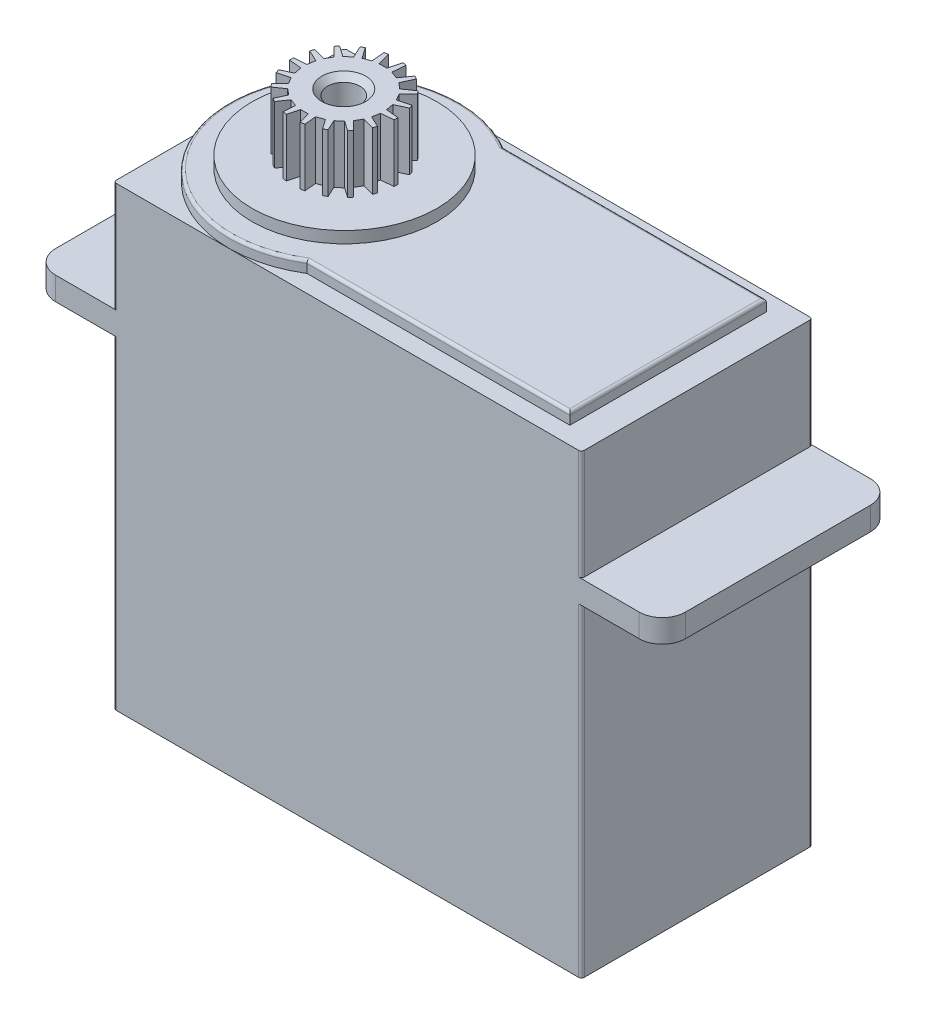
SolidWorks part; units mm, degrees
ref_plane "Plan de face" through (0, 0, 0) normal (0, 0, 1) x (1, 0, 0)
ref_plane "Plan de dessus" through (0, 0, 0) normal (0, 1, 0) x (1, 0, 0)
ref_plane "Plan de droite" through (0, 0, 0) normal (1, 0, 0) x (0, 0, -1)
sketch "Esquisse1" plane through (0, 0, 0) normal (0, 0, 1) x (1, 0, 0)
  line L1 (-20.25, -19.75) -> (20.25, -19.75)
  line L2 (-20.25, -19.75) -> (-20.25, 19.75)
  line L3 (-20.25, 19.75) -> (20.25, 19.75)
  line L4 (20.25, -19.75) -> (20.25, 19.75)
  line L5 (-20.25, -19.75) -> (20.25, 19.75) construction
  line L6 (-20.25, 19.75) -> (20.25, -19.75) construction
  point P0 (0, 0)
  dimension "D1" = 40.5
  dimension "D2" = 39.5
extrude "Boss.-Extru.1" add sketch "Esquisse1" along normal blind 20
sketch "Esquisse2" plane through (-20.25, 0, 0) normal (-1, 0, 0) x (0, 0, 1)
  line L0 (0, 8.25) -> (20, 8.25)
  line L1 (0, 19.75) -> (0, -19.75) construction
  line L2 (20, 19.75) -> (20, -19.75) construction
  line L3 (20, -19.75) -> (0, -19.75) construction
  line L4 (0, 10.25) -> (20, 10.25)
  line L5 (0, 8.25) -> (0, 10.25)
  line L6 (20, 8.25) -> (20, 10.25)
  dimension "D1" = 28
  dimension "D2" = 2
extrude "Boss.-Extru.2" add sketch "Esquisse2" along normal blind 7
sketch "Esquisse3" plane through (20.25, 0, 0) normal (1, 0, 0) x (0, 0, -1)
  line L1 (-20, -19.75) -> (0, -19.75) construction
  line L7 (-20, 8.25) -> (0, 8.25)
  line L8 (-20, -19.75) -> (-20, 19.75) construction
  line L9 (0, -19.75) -> (0, 19.75) construction
  line L10 (0, 8.25) -> (0, 10.25)
  line L11 (0, 10.25) -> (-20, 10.25)
  line L12 (-20, 10.25) -> (-20, 8.25)
  dimension "D1" = 28
  dimension "D2" = 2
extrude "Boss.-Extru.3" add sketch "Esquisse3" along normal blind 7
fillet "Congé1" radius 2 4 edges at (27.25, 9.25, 0) (27.25, 9.25, 20) (-27.25, 9.25, 0) (-27.25, 9.25, 20)
sketch "Esquisse4" plane through (0, 19.75, 0) normal (0, 1, 0) x (1, 0, 0)
  line L0 (-20.25, -10) -> (20.25, -10) construction
  line L1 (-20.25, -20) -> (-20.25, 0) construction
  line L2 (20.25, 0) -> (20.25, -20) construction
  line L3 (17.75, -1.5) -> (17.75, -18.5)
  line L4 (20.25, 0) -> (-20.25, 0) construction
  line L5 (20.25, -20) -> (-20.25, -20) construction
  line L6 (17.75, -1.5) -> (-5.0016, -1.5)
  line L7 (17.75, -18.5) -> (-5.0016, -18.5)
  arc A0 (-5.0016, -1.5) -> (-5.0016, -18.5) centre (-10.25, -10) ccw
  dimension "D1" = 10
  dimension "D2" = 1.5
  dimension "D3" = 1.5
  dimension "D4" = 2.5
extrude "Boss.-Extru.4" add sketch "Esquisse4" along normal blind 1
sketch "Esquisse6" plane through (0, 20.75, 0) normal (0, 1, 0) x (1, 0, 0)
  circle A0 centre (-10.25, -10) radius 8
extrude "Boss.-Extru.5" add sketch "Esquisse6" along normal blind 1
sketch "Esquisse7" plane through (0, 21.75, 0) normal (0, 1, 0) x (1, 0, 0)
  circle A0 centre (-10.25, -10) radius 4.5
extrude "Boss.-Extru.6" add sketch "Esquisse7" along normal blind 5
sketch "Esquisse8" plane through (0, 26.75, 0) normal (0, 1, 0) x (1, 0, 0)
  line L0 (-10.6064, -6.6566) -> (-10.9035, -5.5477)
  line L3 (-10.6064, -6.6566) -> (-9.9401, -6.6566)
  line L7 (-9.9401, -6.6566) -> (-9.6413, -5.5414)
  circle A1 centre (-10.25, -10) radius 4.5
  arc A2 (-9.6413, -5.5414) -> (-10.9035, -5.5477) centre (-10.25, -10) ccw
  point P0 (-10.25, -5.5)
  dimension "D2" = 255
  dimension "D3" = 255
  dimension "D1" = 0
extrude "Enlèv. mat.-Extru.2" cut sketch "Esquisse8" against normal blind 5
pattern_circular "Répétition circulaire2" count 18 over 360 about axis through (-10.2496, 0, 10.0706) along (0, 1, 0) of "Enlèv. mat.-Extru.2"
sketch "Esquisse9" plane through (0, 26.75, 0) normal (0, 1, 0) x (1, 0, 0)
  line L0 (-10.2732, -6.6566) -> (-10.226, -13.4845) construction
  line L1 (-10.6064, -6.6566) -> (-9.9401, -6.6566) construction
  line L2 (-9.8929, -13.4845) -> (-10.5591, -13.4845) construction
  circle A0 centre (-10.2496, -10.0706) radius 1.4
extrude "Enlèv. mat.-Extru.3" cut sketch "Esquisse9" against normal blind 5
chamfer "Chanfrein1" distance 0.5 angle 45 1 edges at (-10.2496, 26.75, 11.4706)
fillet "Congé3" radius 0.25 4 edges at (17.75, 20.75, 10) (6.3742, 20.75, 18.5) (-20.2398, 20.75, 10) (6.3742, 20.75, 1.5)
fillet "Congé4" radius 0.25 8 edges at (20.25, -5.75, 0) (20.25, 15, 0) (20.25, -5.75, 20) (20.25, 15, 20) (-20.25, 15, 0) (-20.25, -5.75, 0) (-20.25, -5.75, 20) (-20.25, 15, 20)
